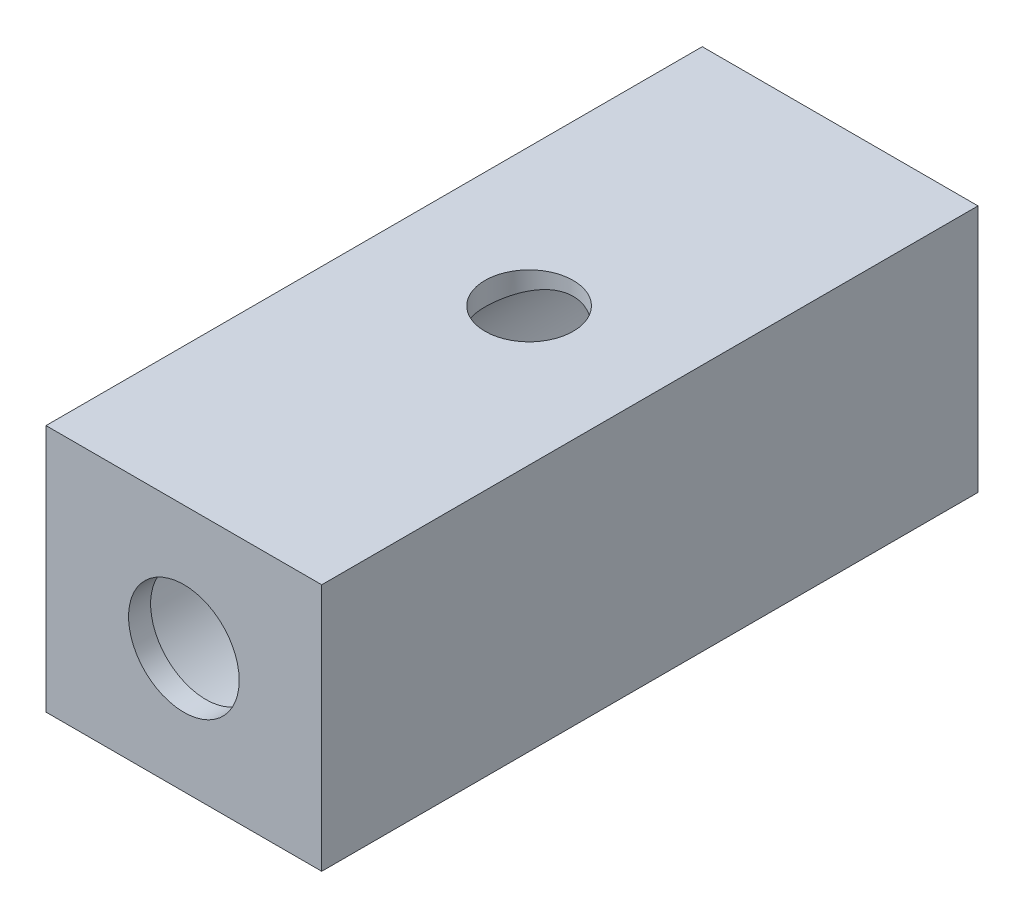
SolidWorks part; units mm, degrees
ref_plane "Front Plane" through (0, 0, 0) normal (0, 0, 1) x (1, 0, 0)
ref_plane "Top Plane" through (0, 0, 0) normal (0, 1, 0) x (1, 0, 0)
ref_plane "Right Plane" through (0, 0, 0) normal (1, 0, 0) x (0, 0, -1)
sketch "Sketch1" plane through (0, 0, 0) normal (0, 0, 1) x (1, 0, 0)
  line L1 (0, 0) -> (63.5, 0)
  line L2 (0, 0) -> (0, 57.15)
  line L3 (0, 57.15) -> (63.5, 57.15)
  line L4 (63.5, 0) -> (63.5, 57.15)
  dimension "D1" = 57.15
  dimension "D2" = 63.5
extrude "Boss-Extrude5" add sketch "Sketch1" along normal blind 148.59
sketch "Sketch5" plane through (0, 0, 148.59) normal (0, 0, 1) x (1, 0, 0)
  line L1 (0, 57.15) -> (63.5, 57.15)
  line L2 (0, 57.15) -> (0, 0)
  line L3 (0, 0) -> (63.5, 0)
  line L4 (63.5, 57.15) -> (63.5, 0)
  circle A0 centre (31.75, 28.575) radius 25.4
  dimension "D1" = 28.575
  dimension "D2" = 31.75
  dimension "D3" = 50.8
extrude "Cut-Extrude4" cut sketch "Sketch5" against normal blind 146.05 flip side to cut
sketch "Sketch8" plane through (0, 0, 148.59) normal (0, 0, 1) x (1, 0, 0)
  line L1 (0, 57.15) -> (63.5, 57.15)
  line L2 (0, 57.15) -> (0, 0)
  line L3 (0, 0) -> (63.5, 0)
  line L4 (63.5, 57.15) -> (63.5, 0)
  circle A0 centre (31.75, 28.575) radius 12.7404
extrude "Boss-Extrude6" add sketch "Sketch8" along normal mid plane 5.08
sketch "Sketch9" plane through (0, 57.15, 0) normal (0, 1, 0) x (1, 0, 0)
  line L0 (0, -151.13) -> (0, 0) construction
  line L1 (63.5, -151.13) -> (0, -151.13) construction
  circle A0 centre (31.75, -71.628) radius 10.16
  dimension "D1" = 20.32
  dimension "D2" = 31.75
  dimension "D3" = 79.502
extrude "Cut-Extrude5" cut sketch "Sketch9" against normal up to next
sketch "Sketch10" plane through (0, 0, 0) normal (0, -1, 0) x (1, 0, 0)
  line L0 (0, 151.13) -> (0, 0) construction
  line L1 (0, 151.13) -> (63.5, 151.13) construction
  line L2 (63.5, 151.13) -> (63.5, 0) construction
  line L3 (0, 0) -> (63.5, 0) construction
  circle A0 centre (17.78, 81.534) radius 10.16
  circle A1 centre (44.45, 125.73) radius 10.16
  circle A2 centre (44.45, 50.8) radius 10.16
  point P10 (31.75, 151.13)
  dimension "D1" = 20.32
  dimension "D2" = 20.32
  dimension "D3" = 20.32
  dimension "D4" = 17.78
  dimension "D5" = 69.596
  dimension "D6" = 25.4
  dimension "D7" = 19.05
  dimension "D8" = 19.05
  dimension "D9" = 50.8
extrude "Cut-Extrude6" cut sketch "Sketch10" against normal up to next
